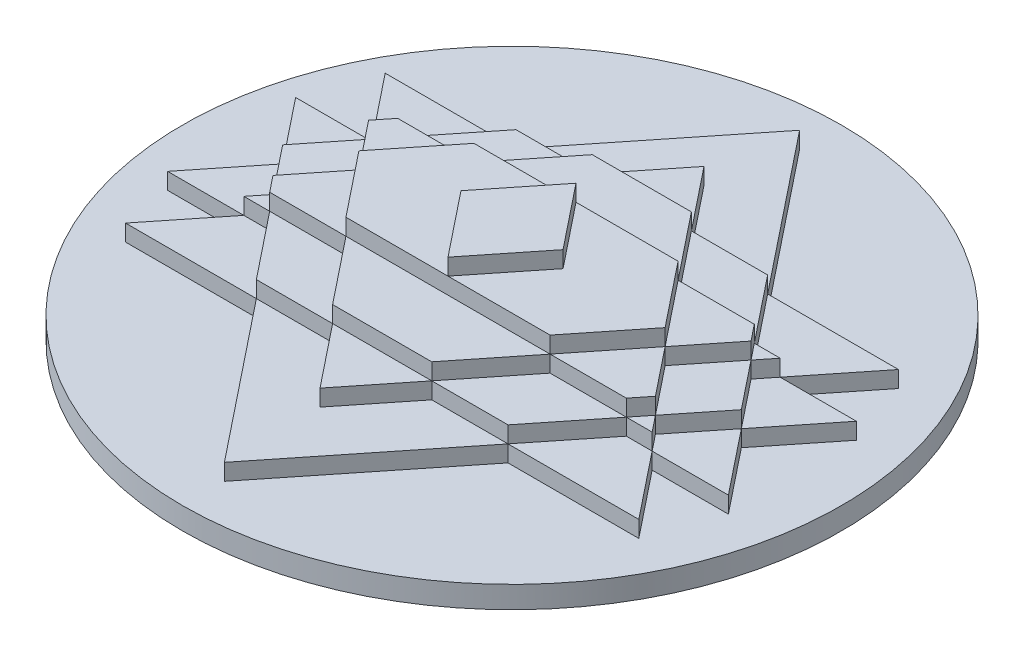
SolidWorks part; units mm, degrees
ref_plane "Front Plane" through (0, 0, 0) normal (0, 0, 1) x (1, 0, 0)
ref_plane "Top Plane" through (0, 0, 0) normal (0, 1, 0) x (1, 0, 0)
ref_plane "Right Plane" through (0, 0, 0) normal (1, 0, 0) x (0, 0, -1)
sketch "Sketch1" plane through (0, 0, 0) normal (0, 1, 0) x (1, 0, 0)
  line L0 (0, 261.8) -> (0, -261.8) construction
  line L1 (0, 261.8) -> (-255.2361, -58.256)
  line L2 (-255.2361, -58.256) -> (255.2361, -58.256)
  line L3 (255.2361, -58.256) -> (0, 261.8)
  line L4 (0, -261.8) -> (-255.2361, 58.256)
  line L5 (-255.2361, 58.256) -> (255.2361, 58.256)
  line L6 (255.2361, 58.256) -> (0, -261.8)
  line L7 (0, 58.256) -> (-92.9152, -58.256)
  line L8 (-92.9152, -58.256) -> (92.9152, -58.256)
  line L9 (92.9152, -58.256) -> (0, 58.256)
  line L10 (0, -58.256) -> (-92.9152, 58.256)
  line L11 (-92.9152, 58.256) -> (92.9152, 58.256)
  line L12 (92.9152, 58.256) -> (0, -58.256)
  line L16 (0, -174.7679) -> (-233.612, 118.1722)
  line L17 (-233.612, 118.1722) -> (233.612, 118.1722)
  line L18 (233.612, 118.1722) -> (0, -174.7679)
  line L19 (0, 174.7679) -> (-233.612, -118.1722)
  line L20 (-233.612, -118.1722) -> (233.612, -118.1722)
  line L21 (233.612, -118.1722) -> (0, 174.7679)
  line L22 (-46.4576, 0) -> (46.4576, 0)
  circle A0 centre (0, 0) radius 261.8
  circle A1 centre (0, 0) radius 300
  dimension "D1" = 523.6
  dimension "D8" = 600
  dimension "D2" = 51.429
  dimension "D3" = 51.429
  dimension "D4" = 51.429
  dimension "D5" = 51.429
  dimension "D6" = 51.429
  dimension "D7" = 51.429
extrude "Boss-Extrude1" add sketch "Sketch1" against normal blind 10 contours A1 A0 | L6 A0 L20 | L20 L21 L2 L6 | L21 A0 L2 | L21 L2 L3 L6 | L3 A0 L6 | L5 L18 L3 L6 | L5 A0 L18 | L17 A0 L3 | L3 L0 L21 L17 | L0 L1 L17 L19 | L1 A0 L17 | L21 L0 L17 | L0 L19 L17 | L21 L6 L3 L18 | L6 L21 L18 L2 | L18 L20 L6 L2 | L2 L21 L6 | L18 L0 L6 L20 | L0 L16 L20 L4 | L20 A0 L4 | L19 L20 L4 L2 | L2 A0 L19 | L4 L19 L2 | L16 L19 L4 L2 | L4 L20 L16 L2 | L19 L4 L1 L2 | L19 L16 L1 L4 | L4 A0 L1 | L1 L16 L5 L4 | L16 A0 L5 | L17 L16 L5 L1 | L16 L1 L5
sketch "Sketch2" plane through (0, -10, 0) normal (0, -1, 0) x (1, 0, 0)
  circle A0 centre (0, 0) radius 300
extrude "Boss-Extrude2" add sketch "Sketch2" along normal blind 10
sketch "Sketch3" plane through (0, 0, 0) normal (0, 1, 0) x (1, 0, 0)
  line L0 (0, 261.8) -> (0, -261.8) construction
  line L1 (0, 261.8) -> (-255.2361, -58.256)
  line L2 (-255.2361, -58.256) -> (255.2361, -58.256)
  line L3 (255.2361, -58.256) -> (0, 261.8)
  line L4 (0, -261.8) -> (-255.2361, 58.256)
  line L5 (-255.2361, 58.256) -> (255.2361, 58.256)
  line L6 (255.2361, 58.256) -> (0, -261.8)
  line L7 (0, 58.256) -> (-92.9152, -58.256)
  line L8 (-92.9152, -58.256) -> (92.9152, -58.256)
  line L9 (92.9152, -58.256) -> (0, 58.256)
  line L10 (0, -58.256) -> (-92.9152, 58.256)
  line L11 (-92.9152, 58.256) -> (92.9152, 58.256)
  line L12 (92.9152, 58.256) -> (0, -58.256)
  line L13 (0, -174.7679) -> (-233.612, 118.1722)
  line L14 (-233.612, 118.1722) -> (233.612, 118.1722)
  line L15 (233.612, 118.1722) -> (0, -174.7679)
  line L16 (0, 174.7679) -> (-233.612, -118.1722)
  line L17 (-233.612, -118.1722) -> (233.612, -118.1722)
  line L18 (233.612, -118.1722) -> (0, 174.7679)
  line L19 (-46.4576, 0) -> (46.4576, 0)
  circle A1 centre (0, 0) radius 261.8
  circle A2 centre (0, 0) radius 300
  dimension "D1" = 523.6
  dimension "D8" = 600
  dimension "D2" = 51.429
  dimension "D3" = 51.429
  dimension "D4" = 51.429
  dimension "D5" = 51.429
  dimension "D6" = 51.429
  dimension "D7" = 51.429
extrude "Boss-Extrude4" add sketch "Sketch3" along normal blind 15 contours L0 L13 L17 L4 | L15 L0 L6 L17 | L17 L18 L2 L6 | L18 L2 L3 L6 | L5 L15 L3 L6 | L15 L14 L3 L5 | L3 L0 L18 L14 | L0 L1 L14 L16 | L14 L13 L5 L1 | L1 L13 L5 L4 | L16 L4 L1 L2 | L16 L17 L4 L2 | L13 L1 L5 | L16 L13 L1 L4 | L4 L16 L2 | L13 L16 L4 L2 | L4 L17 L13 L2 | L0 L17 L13 | L17 L0 L15 | L15 L17 L6 L2 | L6 L18 L15 L2 | L2 L18 L6 | L18 L6 L3 L15 | L18 L15 L3 L5 | L15 L5 L3 | L18 L5 L3 L14 | L18 L0 L14 | L0 L16 L14 | L16 L14 L1 L5 | L16 L5 L1 L13 | L10 L16 L13 L7 | L10 L7 L5 | L0 L14 L16 L5 | L14 L0 L5 L18 | L12 L5 L9 | L15 L18 L12 L9 | L9 L12 L8 | L19 L0 L12 | L9 L0 L19 | L0 L7 L19 | L0 L19 L10 | L2 L10 L7 | L0 L2 L13 L17 | L8 L0 L17 L15
sketch "Sketch4" plane through (0, 15, 0) normal (0, 1, 0) x (1, 0, 0)
  line L0 (0, 261.8) -> (0, -261.8) construction
  line L1 (0, 261.8) -> (-255.2361, -58.256)
  line L2 (-255.2361, -58.256) -> (255.2361, -58.256)
  line L3 (255.2361, -58.256) -> (0, 261.8)
  line L4 (0, -261.8) -> (-255.2361, 58.256)
  line L5 (-255.2361, 58.256) -> (255.2361, 58.256)
  line L6 (255.2361, 58.256) -> (0, -261.8)
  line L7 (0, 58.256) -> (-92.9152, -58.256)
  line L8 (-92.9152, -58.256) -> (92.9152, -58.256)
  line L9 (92.9152, -58.256) -> (0, 58.256)
  line L10 (0, -58.256) -> (-92.9152, 58.256)
  line L11 (-92.9152, 58.256) -> (92.9152, 58.256)
  line L12 (92.9152, 58.256) -> (0, -58.256)
  line L13 (0, -174.7679) -> (-233.612, 118.1722)
  line L14 (-233.612, 118.1722) -> (233.612, 118.1722)
  line L15 (233.612, 118.1722) -> (0, -174.7679)
  line L16 (0, 174.7679) -> (-233.612, -118.1722)
  line L17 (-233.612, -118.1722) -> (233.612, -118.1722)
  line L18 (233.612, -118.1722) -> (0, 174.7679)
  line L19 (-46.4576, 0) -> (46.4576, 0)
  circle A0 centre (0, 0) radius 300
  circle A1 centre (0, 0) radius 261.8
  circle A2 centre (0, 0) radius 300 construction
  point P3 (0, 0)
  point P28 (1.5024, -5.2928)
  line M28 (233.612, 118.1722) -> (114.5393, 118.1722)
  line M29 (114.5393, 118.1722) -> (0, 261.8)
  line M30 (0, 261.8) -> (-114.5393, 118.1722)
  line M31 (-114.5393, 118.1722) -> (-233.612, 118.1722)
  dimension "D1" = 523.6
  dimension "D2" = 51.429
  dimension "D3" = 51.429
  dimension "D4" = 51.429
  dimension "D5" = 51.429
  dimension "D6" = 51.429
  dimension "D7" = 51.429
extrude "Boss-Extrude5" add sketch "Sketch4" along normal blind 15 contours L4 L17 L13 L2 | L13 L16 L4 L2 | L4 L16 L2 | L16 L13 L1 L4 | L13 L1 L5 | L16 L5 L1 L13 | L16 L14 L1 L5 M30 M31 | L0 L14 L16 L5 | L0 L16 L14 | L18 L0 L14 | L14 L0 L5 L18 | L18 L5 L3 L14 M28 M29 | L18 L15 L3 L5 | L15 L5 L3 | L18 L6 L3 L15 | L6 L18 L15 L2 | L2 L18 L6 | L15 L17 L6 L2 | L8 L0 L17 L15 | L17 L0 L15 | L0 L17 L13 | L0 L2 L13 L17 | L10 L16 L13 L7 | L2 L10 L7 | L10 L7 L5 | L0 L7 L19 | L9 L0 L19 | L19 L0 L12 | L0 L19 L10 | L9 L12 L8 | L15 L18 L12 L9 | L12 L5 L9
sketch "Sketch6" plane through (0, 30, 0) normal (0, 1, 0) x (1, 0, 0)
  line L0 (0, 261.8) -> (0, -261.8) construction
  line L1 (0, 261.8) -> (-255.2361, -58.256)
  line L2 (-255.2361, -58.256) -> (255.2361, -58.256)
  line L3 (255.2361, -58.256) -> (0, 261.8)
  line L4 (0, -261.8) -> (-255.2361, 58.256)
  line L5 (-255.2361, 58.256) -> (255.2361, 58.256)
  line L6 (255.2361, 58.256) -> (0, -261.8)
  line L7 (0, 58.256) -> (-92.9152, -58.256)
  line L8 (-92.9152, -58.256) -> (92.9152, -58.256)
  line L9 (92.9152, -58.256) -> (0, 58.256)
  line L10 (0, -58.256) -> (-92.9152, 58.256)
  line L11 (-92.9152, 58.256) -> (92.9152, 58.256)
  line L12 (92.9152, 58.256) -> (0, -58.256)
  line L13 (0, -174.7679) -> (-233.612, 118.1722)
  line L14 (-233.612, 118.1722) -> (233.612, 118.1722)
  line L15 (233.612, 118.1722) -> (0, -174.7679)
  line L16 (0, 174.7679) -> (-233.612, -118.1722)
  line L17 (-233.612, -118.1722) -> (233.612, -118.1722)
  line L18 (233.612, -118.1722) -> (0, 174.7679)
  line L19 (-46.4576, 0) -> (46.4576, 0)
  line L20 (-45.1336, -118.1722) -> (45.1336, -118.1722)
  circle A0 centre (0, 0) radius 300
  circle A1 centre (0, 0) radius 300
  circle A2 centre (0, 0) radius 261.8
  dimension "D1" = 523.6
  dimension "D2" = 51.429
  dimension "D3" = 51.429
  dimension "D4" = 51.429
  dimension "D5" = 51.429
  dimension "D6" = 51.429
  dimension "D7" = 51.429
extrude "Boss-Extrude11" add sketch "Sketch6" along normal blind 15 contours L0 L2 L13 L17 | L8 L0 L20 L15 | L6 L18 L15 L2 | L15 L18 L12 L9 | L18 L15 L3 L5 | L14 L0 L5 L18 | L0 L14 L16 L5 | L10 L16 L13 L7 | L16 L5 L1 L13 | L13 L16 L4 L2 | L2 L10 L7 | L9 L12 L8 | L19 L0 L12 | L0 L19 L10 | L0 L7 L19 | L9 L0 L19 | L12 L5 L9 | L10 L7 L5
sketch "Sketch10" plane through (0, 45, 0) normal (0, 1, 0) x (1, 0, 0)
  line L0 (0, 261.8) -> (0, -261.8) construction
  line L1 (0, 261.8) -> (-255.2361, -58.256)
  line L2 (-255.2361, -58.256) -> (255.2361, -58.256)
  line L3 (255.2361, -58.256) -> (0, 261.8)
  line L4 (0, -261.8) -> (-255.2361, 58.256)
  line L5 (-255.2361, 58.256) -> (255.2361, 58.256)
  line L6 (255.2361, 58.256) -> (0, -261.8)
  line L7 (0, 58.256) -> (-92.9152, -58.256)
  line L8 (-92.9152, -58.256) -> (92.9152, -58.256)
  line L9 (92.9152, -58.256) -> (0, 58.256)
  line L10 (0, -58.256) -> (-92.9152, 58.256)
  line L11 (-92.9152, 58.256) -> (92.9152, 58.256)
  line L12 (92.9152, 58.256) -> (0, -58.256)
  line L13 (0, -174.7679) -> (-233.612, 118.1722)
  line L14 (-233.612, 118.1722) -> (233.612, 118.1722)
  line L15 (233.612, 118.1722) -> (0, -174.7679)
  line L16 (0, 174.7679) -> (-233.612, -118.1722)
  line L17 (-233.612, -118.1722) -> (233.612, -118.1722)
  line L18 (233.612, -118.1722) -> (0, 174.7679)
  line L19 (-46.4576, 0) -> (46.4576, 0)
  circle A0 centre (0, 0) radius 300
  circle A1 centre (0, 0) radius 300
  circle A2 centre (0, 0) radius 261.8
  point P0 (0, 0)
  point P26 (0, 0)
  point P27 (0, 0)
  point P28 (0, 0)
  dimension "D1" = 523.6
  dimension "D2" = 51.429
  dimension "D3" = 51.429
  dimension "D4" = 51.429
  dimension "D5" = 51.429
  dimension "D6" = 51.429
  dimension "D7" = 51.429
extrude "Boss-Extrude12" add sketch "Sketch10" along normal blind 15 contours L10 L16 L13 L7 | L10 L7 L5 | L12 L5 L9 | L15 L18 L12 L9 | L9 L12 L8 | L9 L0 L19 | L0 L7 L19 | L0 L19 L10 | L19 L0 L12 | L2 L10 L7
sketch "Sketch11" plane through (0, 60, 0) normal (0, 1, 0) x (1, 0, 0)
  line L0 (0, 261.8) -> (0, -261.8) construction
  line L1 (0, 261.8) -> (-255.2361, -58.256)
  line L2 (-255.2361, -58.256) -> (255.2361, -58.256)
  line L3 (255.2361, -58.256) -> (0, 261.8)
  line L4 (0, -261.8) -> (-255.2361, 58.256)
  line L5 (-255.2361, 58.256) -> (255.2361, 58.256)
  line L6 (255.2361, 58.256) -> (0, -261.8)
  line L7 (0, 58.256) -> (-92.9152, -58.256)
  line L8 (-92.9152, -58.256) -> (92.9152, -58.256)
  line L9 (92.9152, -58.256) -> (0, 58.256)
  line L10 (0, -58.256) -> (-92.9152, 58.256)
  line L11 (-92.9152, 58.256) -> (92.9152, 58.256)
  line L12 (92.9152, 58.256) -> (0, -58.256)
  line L13 (0, -174.7679) -> (-233.612, 118.1722)
  line L14 (-233.612, 118.1722) -> (233.612, 118.1722)
  line L15 (233.612, 118.1722) -> (0, -174.7679)
  line L16 (0, 174.7679) -> (-233.612, -118.1722)
  line L17 (-233.612, -118.1722) -> (233.612, -118.1722)
  line L18 (233.612, -118.1722) -> (0, 174.7679)
  line L19 (-46.4576, 0) -> (46.4576, 0)
  circle A0 centre (0, 0) radius 300
  circle A1 centre (0, 0) radius 300
  circle A2 centre (0, 0) radius 261.8
  point P3 (0, 0)
  point P27 (0, 0)
  dimension "D1" = 523.6
  dimension "D2" = 51.429
  dimension "D3" = 51.429
  dimension "D4" = 51.429
  dimension "D5" = 51.429
  dimension "D6" = 51.429
  dimension "D7" = 51.429
extrude "Boss-Extrude13" add sketch "Sketch11" along normal blind 15 contours L0 L7 L19 | L9 L0 L19 | L19 L0 L12 | L0 L19 L10
